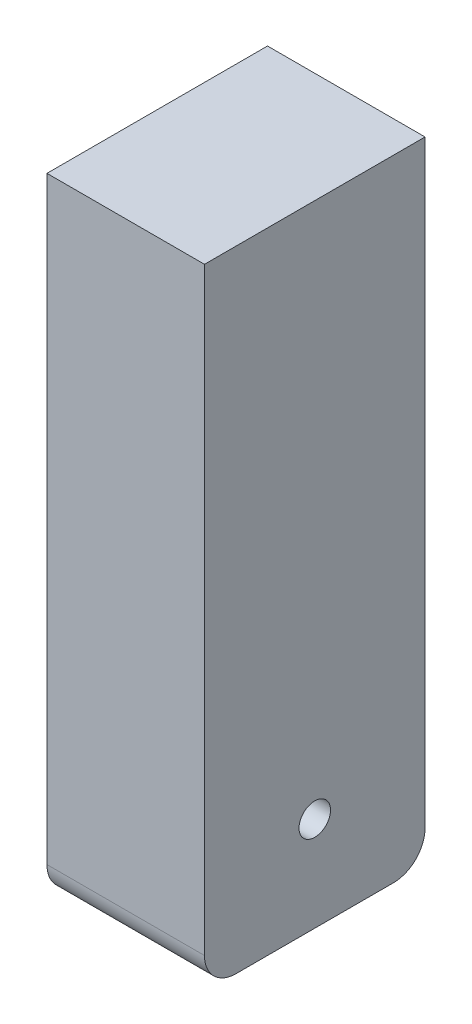
SolidWorks part; units mm, degrees
ref_plane "Front Plane" through (0, 0, 0) normal (0, 0, 1) x (1, 0, 0)
ref_plane "Top Plane" through (0, 0, 0) normal (0, 1, 0) x (1, 0, 0)
ref_plane "Right Plane" through (0, 0, 0) normal (1, 0, 0) x (0, 0, -1)
sketch "Sketch1" plane through (0, 0, 0) normal (0, 1, 0) x (1, 0, 0)
  line L1 (-25, 35) -> (25, 35)
  line L2 (-25, 35) -> (-25, -35)
  line L3 (-25, -35) -> (25, -35)
  line L4 (25, 35) -> (25, -35)
  line L5 (-25, 35) -> (25, -35) construction
  line L6 (-25, -35) -> (25, 35) construction
  point P0 (0, 0)
extrude "Boss-Extrude1" add sketch "Sketch1" along normal blind 200
sketch "Sketch2" plane through (-25, 0, 0) normal (-1, 0, 0) x (0, 0, 1)
  circle A0 centre (0, 30) radius 5
extrude "Cut-Extrude1" cut sketch "Sketch2" against normal blind 200
fillet "Fillet1" radius 10 2 edges at (0, 0, -35) (0, 0, 35)
